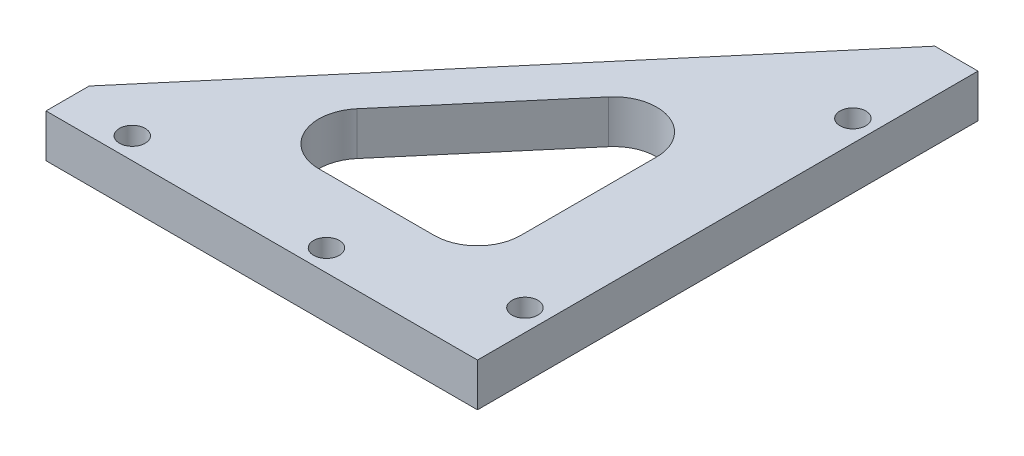
SolidWorks part; units mm, degrees
ref_plane "Front Plane" through (0, 0, 0) normal (0, 0, 1) x (1, 0, 0)
ref_plane "Top Plane" through (0, 0, 0) normal (0, 1, 0) x (1, 0, 0)
ref_plane "Right Plane" through (0, 0, 0) normal (1, 0, 0) x (0, 0, -1)
sketch "Sketch1" plane through (0, 0, 0) normal (0, 1, 0) x (1, 0, 0)
  line L0 (0, 0) -> (63.5, 0)
  line L1 (63.5, 0) -> (63.5, 73.66)
  line L3 (0, 0) -> (0, 6.35)
  line L4 (0, 6.35) -> (57.15, 73.66)
  line L5 (57.15, 73.66) -> (63.5, 73.66)
  line L6 (13.7216, 12.7) -> (50.8, 12.7)
  line L7 (50.8, 12.7) -> (50.8, 56.3701)
  line L8 (50.8, 56.3701) -> (13.7216, 12.7)
  dimension "D1" = 6.35
  dimension "D2" = 63.5
  dimension "D3" = 73.66
  dimension "D4" = 12.7
  dimension "D5" = 12.7
  dimension "D6" = 6.35
extrude "Boss-Extrude1" add sketch "Sketch1" along normal blind 6.35 contours L7 L8 L6 | L4 L5 L1 L0 L3
hole_wizard "#6 Clearance Hole1" positions "Sketch2" profile "Sketch3" hole size "#6" standard "ANSI Inch"
sketch "Sketch2" plane through (0, 6.35, 0) normal (0, 1, 0) x (1, 0, 0)
  line L3 (0, 0) -> (0, 6.35) construction
  line L4 (0, 0) -> (63.5, 0) construction
  line L5 (63.5, 0) -> (63.5, 73.66) construction
  point P0 (9.525, 3.175)
  point P2 (38.1, 3.175)
  point P4 (60.325, 10.16)
  point P6 (60.325, 58.42)
  point P13 (0, 0)
  point P14 (0, 0)
  point P15 (0, 0)
  dimension "D1" = 9.525
  dimension "D2" = 38.1
  dimension "D3" = 3.175
  dimension "D4" = 10.16
  dimension "D5" = 58.42
  dimension "D6" = 3.175
sketch "Sketch3" plane through (9.525, 6.35, -3.175) normal (1, 0, 0) x (0, 0, 1)
  line L0 (0, 0) -> (0, 13.8408)
  line L1 (0, 13.8408) -> (1.8986, 12.7)
  line L2 (1.8986, 12.7) -> (1.8986, 0)
  line L5 (1.8986, 0) -> (0, 0)
  line L10 (0, 13.8408) -> (-1.8987, 12.7) construction
  line L11 (0, -6.35) -> (0, 107.95) construction
  dimension "Hole Dia." = 3.7973
  dimension "Hole Depth" = 12.7
  dimension "Drill Angle" = 118
fillet "Fillet1" radius 6.35 3 edges at (50.8, 3.175, -56.3701) (50.8, 3.175, -12.7) (13.7216, 3.175, -12.7)
